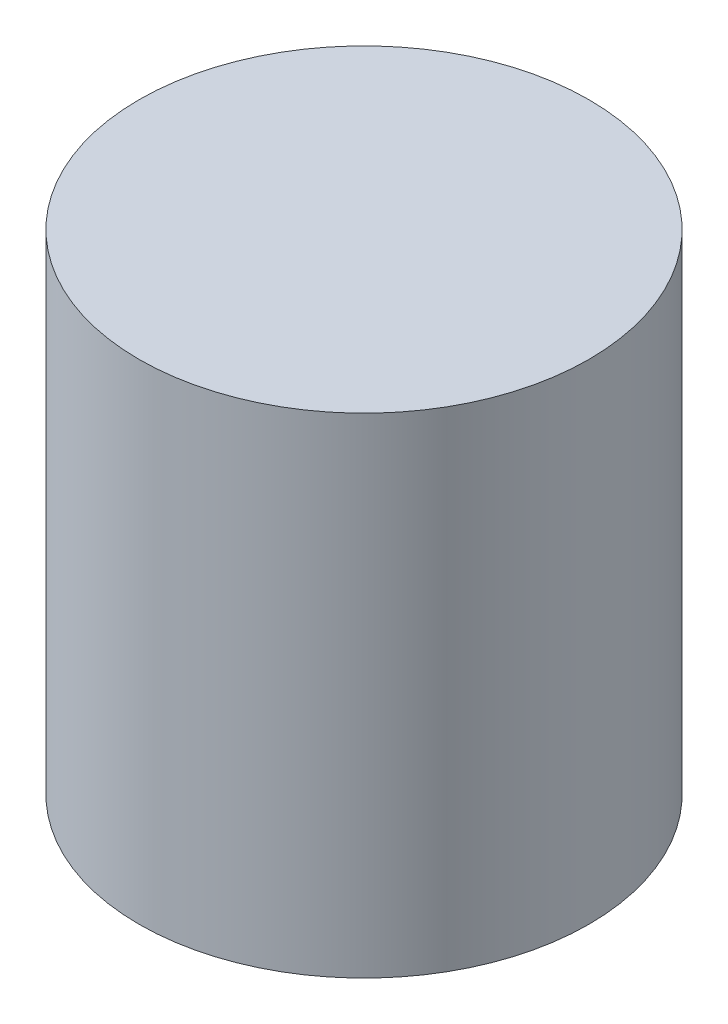
SolidWorks part; units mm, degrees
ref_plane "Front Plane" through (0, 0, 0) normal (0, 0, 1) x (1, 0, 0)
ref_plane "Top Plane" through (0, 0, 0) normal (0, 1, 0) x (1, 0, 0)
ref_plane "Right Plane" through (0, 0, 0) normal (1, 0, 0) x (0, 0, -1)
sketch "Sketch1" plane through (0, 0, 0) normal (0, 1, 0) x (1, 0, 0)
  circle A0 centre (0, 0) radius 2
extrude "Boss-Extrude1" add sketch "Sketch1" along normal blind 4.35
